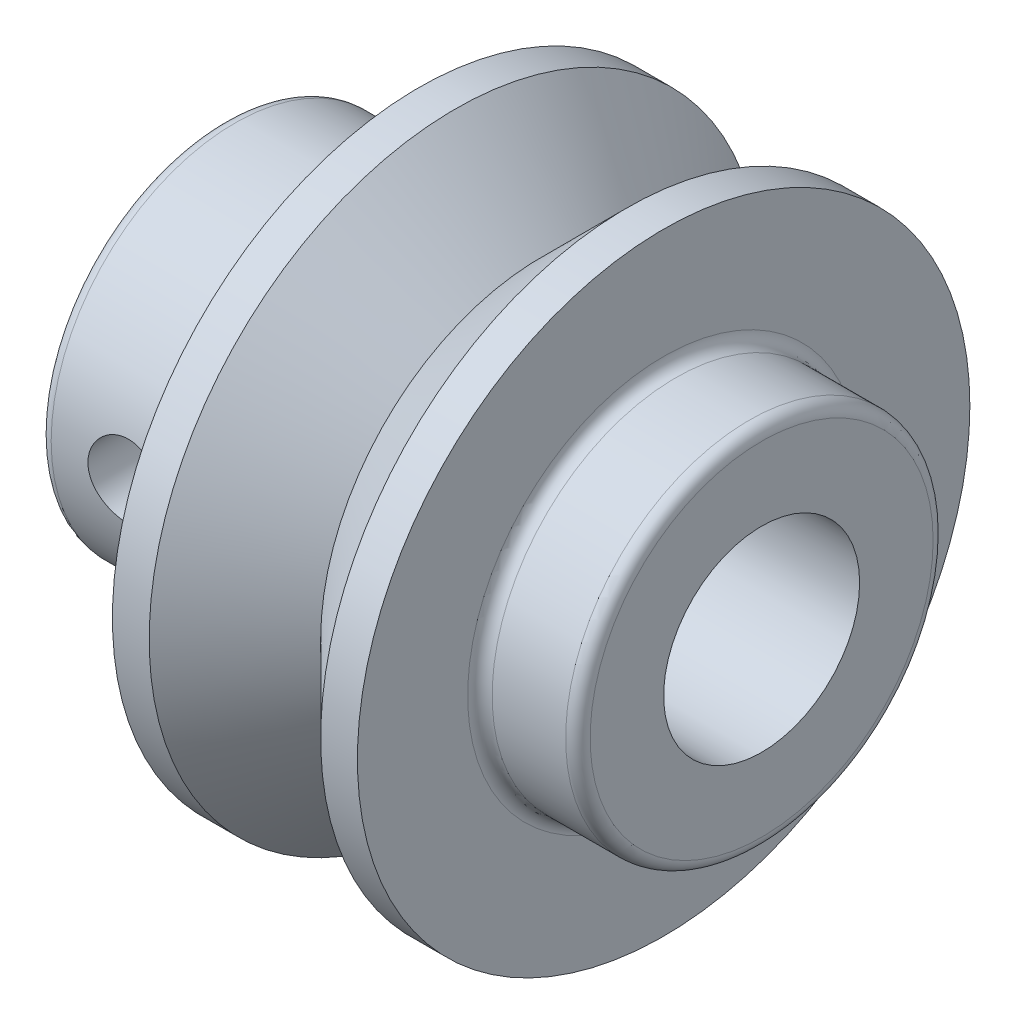
SolidWorks part; units mm, degrees
ref_plane "Front Plane" through (0, 0, 0) normal (0, 0, 1) x (1, 0, 0)
ref_plane "Top Plane" through (0, 0, 0) normal (0, 1, 0) x (1, 0, 0)
ref_plane "Right Plane" through (0, 0, 0) normal (1, 0, 0) x (0, 0, -1)
sketch "Sketch1" plane through (0, 0, 0) normal (0, 0, 1) x (1, 0, 0)
  line L0 (0, 0) -> (0, 7.5)
  line L1 (0, 7.5) -> (8, 7.5)
  line L2 (8, 7.5) -> (8, 12.5)
  line L3 (8, 12.5) -> (9.5, 12.5)
  line L4 (9.5, 12.5) -> (13, 9)
  line L5 (13, 9) -> (16.5, 12.5)
  line L6 (16.5, 12.5) -> (18, 12.5)
  line L7 (18, 12.5) -> (18, 7.5)
  line L8 (18, 7.5) -> (22, 7.5)
  line L9 (22, 7.5) -> (22, 0)
  line L10 (22, 0) -> (0, 0)
  dimension "D1" = 7.5
  dimension "D2" = 8
  dimension "D3" = 4
  dimension "D4" = 12.5
  dimension "D5" = 9
  dimension "D6" = 1.5
revolve "Revolve1" add sketch "Sketch1" angle 360 about L10
sketch "Sketch2" plane through (22, 0, 0) normal (1, 0, 0) x (0, 0, -1)
  circle A0 centre (0, 0) radius 4
  dimension "D1" = 8
extrude "Cut-Extrude1" cut sketch "Sketch2" against normal through all
sketch "Sketch3" plane through (0, 0, 0) normal (0, 0, 1) x (1, 0, 0)
  circle A0 centre (3.5, 0) radius 1.5
  dimension "D1" = 3
  dimension "D2" = 3.5
extrude "Cut-Extrude2" cut sketch "Sketch3" against normal mid plane 40
fillet "Fillet1" radius 0.5 4 edges at (8, 0, -7.5) (0, 0, -7.5) (18, 0, -7.5) (22, 0, -7.5)
